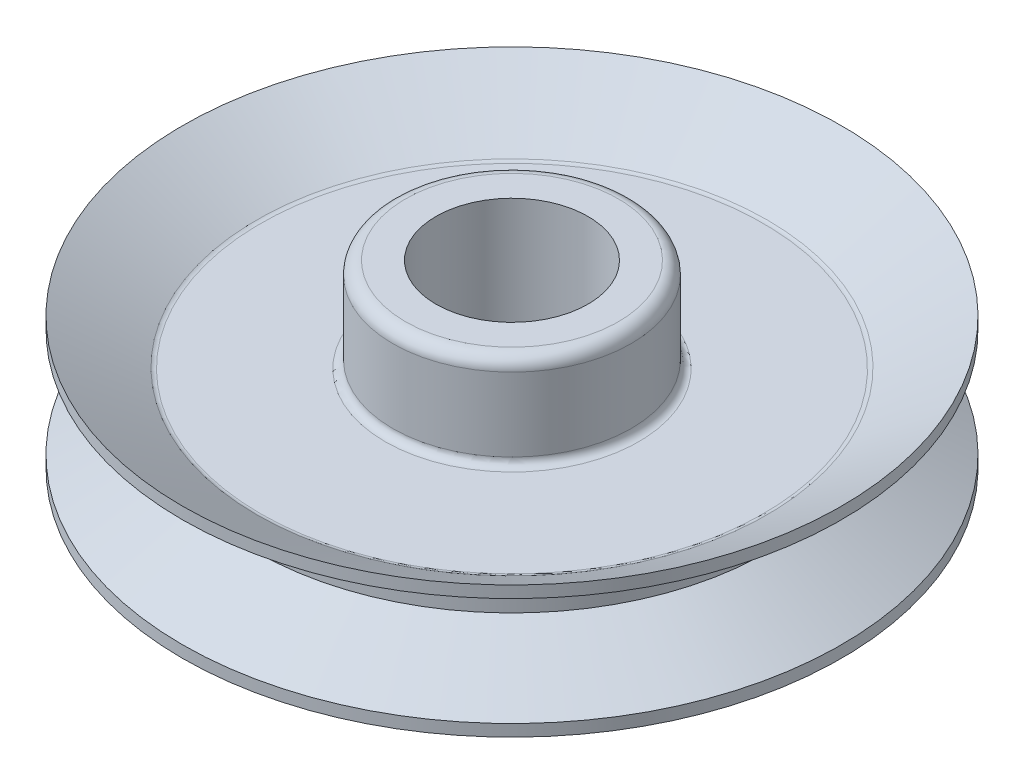
SolidWorks part; units mm, degrees
ref_plane "Front Plane" through (0, 0, 0) normal (0, 0, 1) x (1, 0, 0)
ref_plane "Top Plane" through (0, 0, 0) normal (0, 1, 0) x (1, 0, 0)
ref_plane "Right Plane" through (0, 0, 0) normal (1, 0, 0) x (0, 0, -1)
sketch "Sketch1" plane through (0, 0, 0) normal (1, 0, 0) x (0, 0, -1)
  line L0 (-13, -2.35) -> (-13, -1.8835)
  line L1 (0, 0) -> (0, 2.85) construction
  line L2 (0, 2.85) -> (-13, 2.85) construction
  line L3 (-6.5, 2.85) -> (-6.5, 1.05) construction
  line L4 (-13, 0.25) -> (0, 0.25) construction
  line L5 (-10, -0.55) -> (-13, -2.35)
  line L6 (0, 0) -> (0, -2.6) construction
  line L7 (-13, 2.85) -> (-13, 0.25) construction
  line L8 (0, 1.05) -> (-10, 1.05)
  line L9 (-10, 1.05) -> (-13, 2.85)
  line L10 (0, -0.55) -> (-10, -0.55)
  line L11 (-10.1108, 0.65) -> (-10.1108, -0.15)
  line L13 (-10.1108, -0.15) -> (-13, -1.8835)
  line L15 (-10.1108, 0.65) -> (-13, 2.3835)
  line L16 (-13, 2.3835) -> (-13, 2.85)
  line L17 (0, 1.05) -> (0, -0.55)
  line L18 (-10.1108, -0.15) -> (-13.2058, -2.007) construction
  line L20 (0, -0.15) -> (-10.1108, -0.15) construction
  point P18 (-11.5, 0.25)
  dimension "D3" = 13
  dimension "D4" = 1.8
  dimension "D5" = 2.6
  dimension "D7" = 0.4
revolve "Revolve1" add sketch "Sketch1" angle 360 about L6
sketch "Sketch2" plane through (0, 1.05, 0) normal (0, 1, 0) x (1, 0, 0)
  circle A0 centre (0, 0) radius 4.7
  circle A1 centre (0, 0) radius 3
  dimension "D1" = 9.4
  dimension "D2" = 6
extrude "Boss-Extrude1" add sketch "Sketch2" along normal blind 3.7
sketch "Sketch3" plane through (0, 1.05, 0) normal (0, 1, 0) x (1, 0, 0)
  circle A1 centre (0, 0) radius 3
  circle A2 centre (0, 0) radius 3
  dimension "D1" = 0
extrude "Cut-Extrude1" cut sketch "Sketch3" against normal through all
ref_plane "Plane1" through (0, 0.25, 0) normal (0, 1, 0) x (1, 0, 0)
mirror "Mirror1" about plane through (0, 0.25, 0) normal (0, 1, 0) of "Boss-Extrude1"
fillet "Fillet1" radius 0.5 2 edges at (0, 4.75, 4.7) (0, -4.25, 4.7)
fillet "Fillet2" radius 0.3 4 edges at (0, -0.55, -4.7) (0, 1.05, 4.7) (0, -0.55, 10) (0, 1.05, 10)
